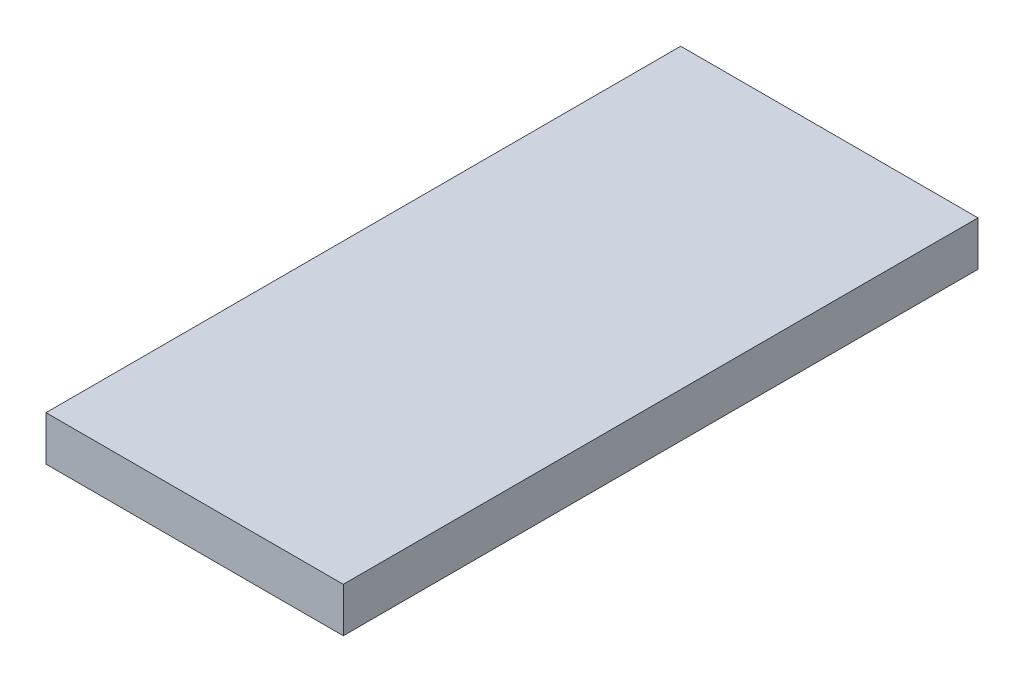
SolidWorks part; units mm, degrees
ref_plane "前视基准面" through (0, 0, 0) normal (0, 0, 1) x (1, 0, 0)
ref_plane "上视基准面" through (0, 0, 0) normal (0, 1, 0) x (1, 0, 0)
ref_plane "右视基准面" through (0, 0, 0) normal (1, 0, 0) x (0, 0, -1)
sketch "草图1" plane through (0, 0, 0) normal (0, 0, 1) x (1, 0, 0)
  line L1 (-50, -7.5) -> (50, -7.5)
  line L2 (-50, -7.5) -> (-50, 7.5)
  line L3 (-50, 7.5) -> (50, 7.5)
  line L4 (50, -7.5) -> (50, 7.5)
  line L5 (-50, -7.5) -> (50, 7.5) construction
  line L6 (-50, 7.5) -> (50, -7.5) construction
  point P0 (0, 0)
extrude "凸台-拉伸1" add sketch "草图1" along normal blind 213.5
